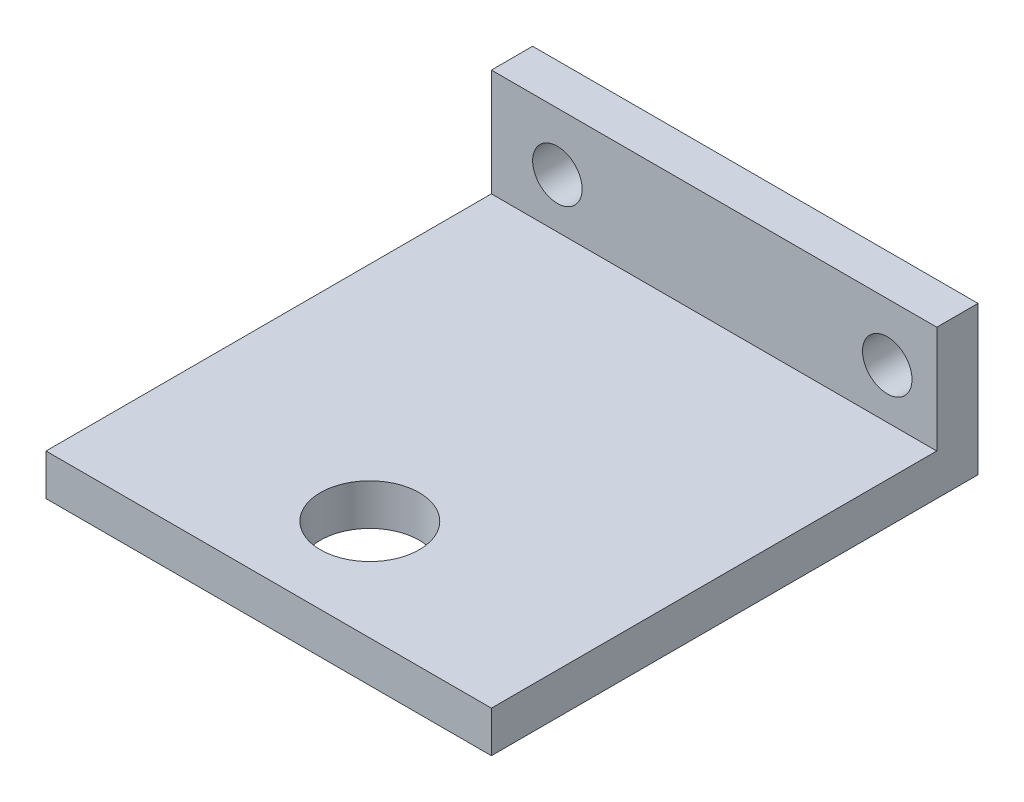
SolidWorks part; units mm, degrees
ref_plane "Plan de face" through (0, 0, 0) normal (0, 0, 1) x (1, 0, 0)
ref_plane "Plan de dessus" through (0, 0, 0) normal (0, 1, 0) x (1, 0, 0)
ref_plane "Plan de droite" through (0, 0, 0) normal (1, 0, 0) x (0, 0, -1)
sketch "Esquisse1" plane through (0, 0, 0) normal (0, 0, 1) x (1, 0, 0)
  line L1 (-27, -9) -> (27, -9)
  line L2 (-27, -9) -> (-27, 9)
  line L3 (-27, 9) -> (27, 9)
  line L4 (27, -9) -> (27, 9)
  line L5 (-27, -9) -> (27, 9) construction
  line L6 (-27, 9) -> (27, -9) construction
  circle A0 centre (-19, 2) radius 3
  circle A1 centre (21, 2) radius 3
  point P0 (0, 0)
  dimension "D3" = 6
  dimension "D1" = 54
  dimension "D2" = 18
  dimension "D4" = 7
  dimension "D5" = 8
  dimension "D6" = 2
extrude "Boss.-Extru.1" add sketch "Esquisse1" along normal blind 59
sketch "Esquisse2" plane through (0, 9, 0) normal (0, 1, 0) x (1, 0, 0)
  line L8 (22, -5) -> (-22, -5)
  line L9 (-22, -5) -> (-22, -54)
  line L10 (-22, -54) -> (22, -54)
  line L11 (22, -54) -> (22, -5)
  line L12 (42.5059, -5) -> (-47.38, -5)
  line L13 (-47.38, -5) -> (-47.38, -79.5648)
  line L14 (-47.38, -79.5648) -> (42.5059, -79.5648)
  line L15 (42.5059, -79.5648) -> (42.5059, -5)
  dimension "D1" = 5
extrude "Enlèv. mat.-Extru.1" cut sketch "Esquisse2" against normal blind 13
sketch "Esquisse3" plane through (0, -4, 0) normal (0, 1, 0) x (1, 0, 0)
  line L0 (-27, -5) -> (-27, -59) construction
  line L1 (27, -5) -> (-27, -5) construction
  circle A0 centre (0, -46.74) radius 6
  dimension "D2" = 12
  dimension "D1" = 27
  dimension "D3" = 41.74
extrude "Enlèv. mat.-Extru.2" cut sketch "Esquisse3" against normal blind 13
